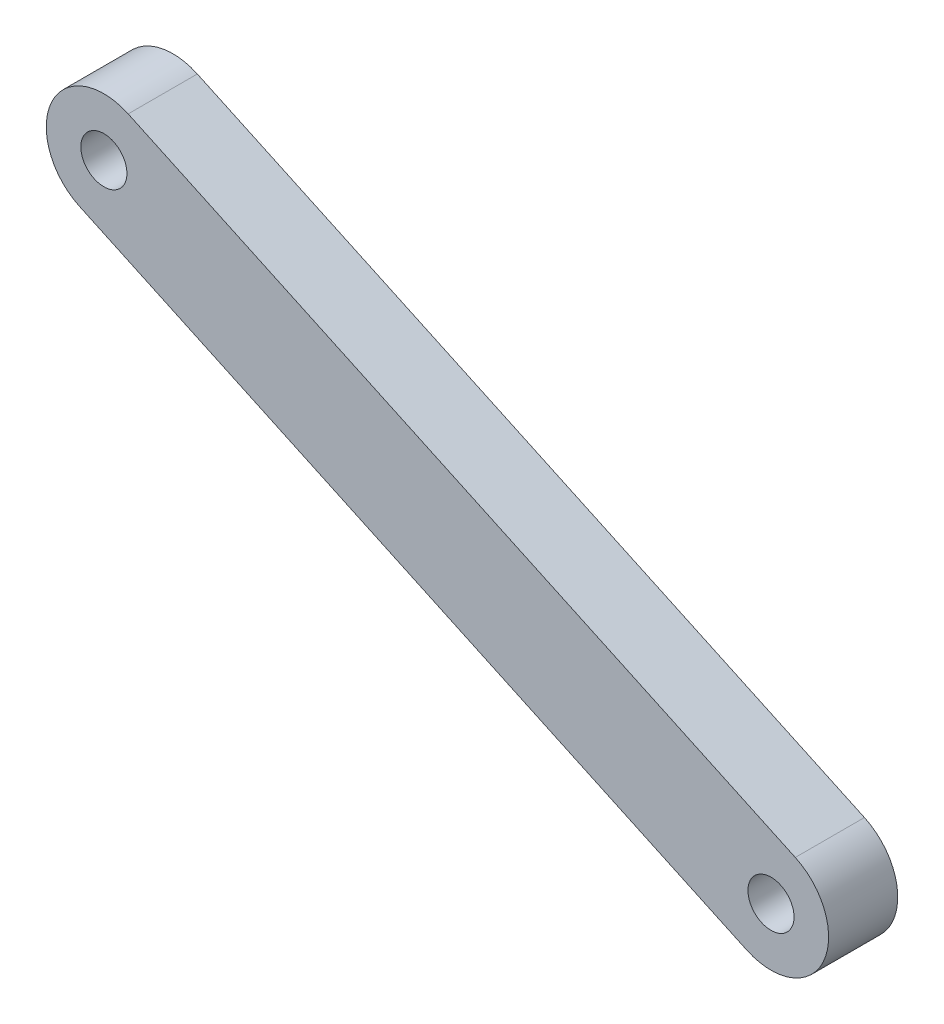
SolidWorks part; units mm, degrees
ref_plane "Спереди" through (0, 0, 0) normal (0, 0, 1) x (1, 0, 0)
ref_plane "Сверху" through (0, 0, 0) normal (0, 1, 0) x (1, 0, 0)
ref_plane "Справа" through (0, 0, 0) normal (1, 0, 0) x (0, 0, -1)
sketch "Sketch1" plane through (0, 0, 0) normal (0, 0, 1) x (1, 0, 0)
  line L0 (12.2142, 44.0917) -> (10.6042, 45.6329) construction
  line L5 (10.6042, 45.6329) -> (8.8374, 47.2581) construction
  line L6 (8.8374, 47.2581) -> (6.9022, 48.9738) construction
  line L7 (6.9022, 48.9738) -> (4.7865, 50.7872) construction
  line L8 (-20.6555, 56.1799) -> (8.2944, 42.7114) construction
  line L9 (-19.601, 58.4466) -> (9.3489, 44.9781)
  line L10 (-21.7101, 53.9132) -> (7.2398, 40.4447)
  line L33 (8.2944, 42.7114) -> (-20.6555, 56.1799) construction
  circle A0 centre (-20.6555, 56.1799) radius 1
  circle A2 centre (8.2944, 42.7114) radius 1
  arc A3 (-19.601, 58.4466) -> (-21.7101, 53.9132) centre (-20.6555, 56.1799) ccw
  arc A4 (7.2398, 40.4447) -> (9.3489, 44.9781) centre (8.2944, 42.7114) ccw
  spline S0 degree 4 poles (12.2142, 44.0917) (10.6042, 45.6329) (8.8374, 47.2581) (6.9022, 48.9738) (4.7865, 50.7872) knots 0 0 0 0 0 1 1 1 1 1 construction
  point P1 (-6.1806, 49.4456)
  dimension "D6" = 2
  dimension "D1" = 5
  dimension "D7" = 10
extrude "Boss-Extrude1" add sketch "Sketch1" along normal blind 3
ref_plane "Plane1" through (17.811, 38.2839, 0) normal (0.4218, 0.9067, 0) x (0.9067, -0.4218, 0)
